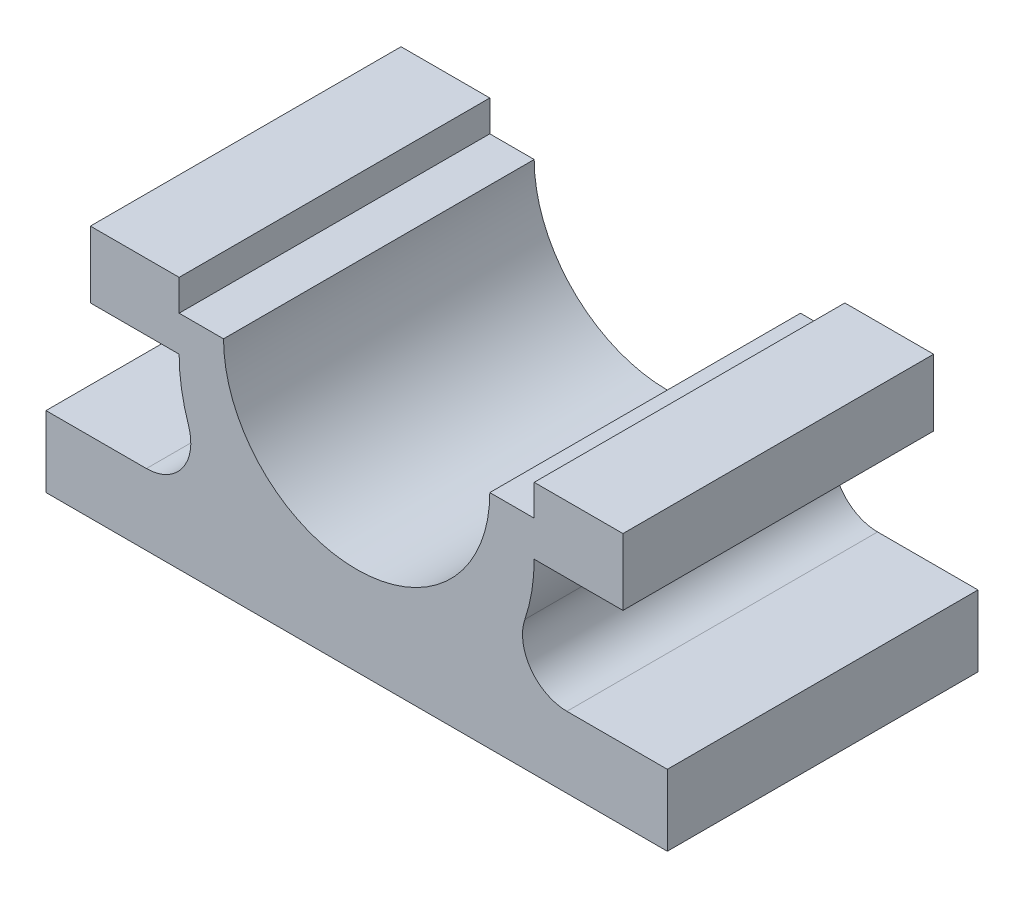
SolidWorks part; units mm, degrees
ref_plane "Alzado" through (0, 0, 0) normal (0, 0, 1) x (1, 0, 0)
ref_plane "Planta" through (0, 0, 0) normal (0, 1, 0) x (1, 0, 0)
ref_plane "Vista lateral" through (0, 0, 0) normal (1, 0, 0) x (0, 0, -1)
sketch "Croquis1" plane through (0, 0, 0) normal (0, 0, 1) x (1, 0, 0)
  line L0 (0, 24.792) -> (0, -273.5145) construction
  line L1 (-90, 0) -> (90, 0) construction
  line L2 (-90, 0) -> (-120, 0)
  line L3 (90, 0) -> (120, 0)
  line L4 (-120, 0) -> (-120, 21)
  line L5 (120, 0) -> (120, 21)
  line L6 (-120, 21) -> (-180, 21)
  line L7 (120, 21) -> (180, 21)
  line L8 (-180, 21) -> (-180, -24)
  line L9 (180, 21) -> (180, -24)
  line L10 (-180, -24) -> (-120, -24)
  line L11 (180, -24) -> (120, -24)
  line L12 (-142.1126, -102) -> (-210, -102)
  line L13 (-210, -102) -> (-210, -150)
  line L14 (-210, -150) -> (210, -150)
  line L15 (142.1126, -102) -> (210, -102)
  line L16 (210, -150) -> (210, -102)
  arc A0 (-90, 0) -> (90, 0) centre (0, 0) ccw
  arc A1 (-120, -24) -> (-113.6901, -62.4) centre (0, -24) ccw
  arc A3 (-142.1126, -102) -> (-113.6901, -62.4) centre (-142.1126, -72) ccw
  arc A4 (113.6901, -62.4) -> (142.1126, -102) centre (142.1126, -72) ccw
  arc A5 (113.6901, -62.4) -> (120, -24) centre (0, -24) ccw
  point P5 (0, 0)
  point P27 (0, -150)
  dimension "D3" = 48
  dimension "D1" = 420
  dimension "D2" = 90
  dimension "D4" = 126
  dimension "D5" = 171
  dimension "D6" = 240
  dimension "D7" = 360
  dimension "D8" = 21
extrude "Saliente-Extruir1" add sketch "Croquis1" along normal mid plane 210
sketch "Croquis5" plane through (0, 0, 0) normal (0, 0, 1) x (1, 0, 0)
  line L30 (-90, 0) -> (-120, 0) construction
  line L31 (90, 0) -> (120, 0) construction
  line L45 (-98.5901, -9) -> (-129, -9)
  line L46 (-129, -9) -> (-129, 12)
  line L47 (-129, 12) -> (-171, 12)
  line L48 (-171, 12) -> (-171, -15)
  line L49 (-171, -15) -> (-110.6345, -15)
  line L50 (-142.1126, -111) -> (-201, -111)
  line L51 (-201, -111) -> (-201, -141)
  line L52 (-201, -141) -> (201, -141)
  line L53 (201, -141) -> (201, -111)
  line L54 (201, -111) -> (142.1126, -111)
  line L55 (110.6345, -15) -> (171, -15)
  line L56 (171, -15) -> (171, 12)
  line L57 (171, 12) -> (129, 12)
  line L58 (129, 12) -> (129, -9)
  line L59 (129, -9) -> (98.5901, -9)
  arc A15 (-110.6345, -15) -> (-105.1633, -59.52) centre (0, -24) ccw
  arc A16 (-142.1126, -111) -> (-105.1633, -59.52) centre (-142.1126, -72) ccw
  arc A17 (105.1633, -59.52) -> (142.1126, -111) centre (142.1126, -72) ccw
  arc A18 (105.1633, -59.52) -> (110.6345, -15) centre (0, -24) ccw
  arc A19 (-98.5901, -9) -> (98.5901, -9) centre (0, 0) ccw
  arc A24 (-99, 0) -> (99, 0) centre (0, 0) ccw
  dimension "D1" = 9
